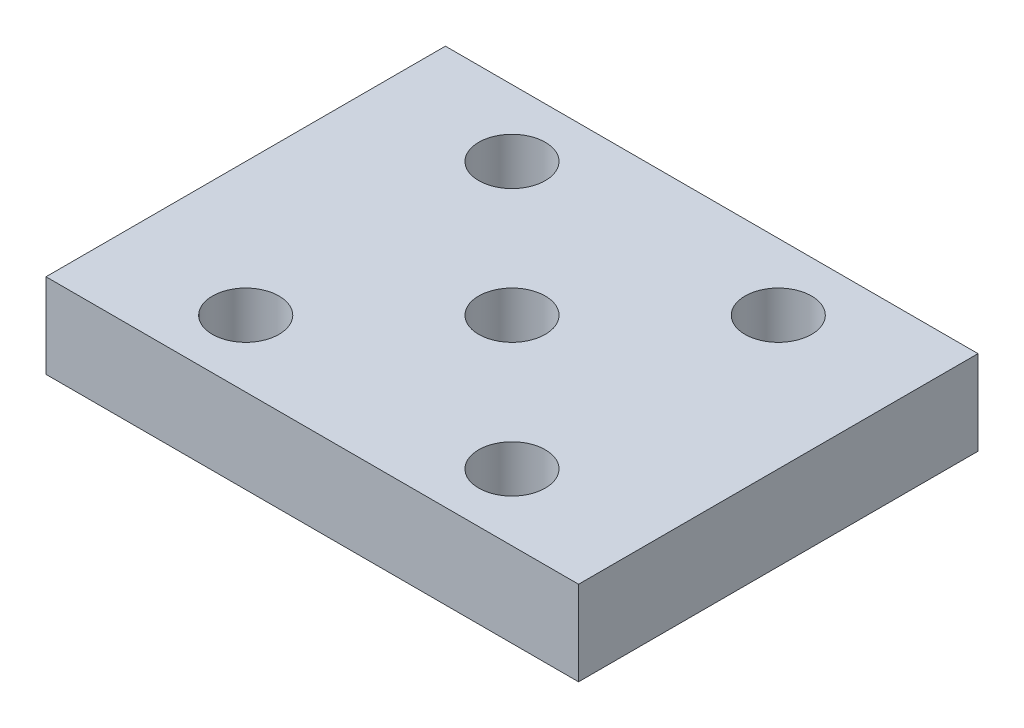
SolidWorks part; units mm, degrees
ref_plane "Front Plane" through (0, 0, 0) normal (0, 0, 1) x (1, 0, 0)
ref_plane "Top Plane" through (0, 0, 0) normal (0, 1, 0) x (1, 0, 0)
ref_plane "Right Plane" through (0, 0, 0) normal (1, 0, 0) x (0, 0, -1)
other "Default"
sketch "Sketch1" plane through (0, 0, 0) normal (0, 1, 0) x (1, 0, 0)
  line L1 (-20, -15) -> (20, -15)
  line L2 (-20, -15) -> (-20, 15)
  line L3 (-20, 15) -> (20, 15)
  line L4 (20, -15) -> (20, 15)
  line L5 (-20, -15) -> (20, 15) construction
  line L6 (-20, 15) -> (20, -15) construction
  line L7 (-10, -10) -> (10, -10) construction
  line L8 (-10, -10) -> (-10, 10) construction
  line L9 (-10, 10) -> (10, 10) construction
  line L10 (10, -10) -> (10, 10) construction
  line L11 (-10, -10) -> (10, 10) construction
  line L12 (-10, 10) -> (10, -10) construction
  circle A1 centre (0, 0) radius 2.5
  circle A3 centre (-10, 10) radius 2.5
  circle A4 centre (10, 10) radius 2.5
  circle A5 centre (10, -10) radius 2.5
  circle A6 centre (-10, -10) radius 2.5
  point P0 (0, 0)
  dimension "D3" = 5
  dimension "D1" = 30
  dimension "D2" = 40
  dimension "D4" = 10
  dimension "D5" = 5
extrude "Boss-Extrude1" add sketch "Sketch1" along normal mid plane 6.35
